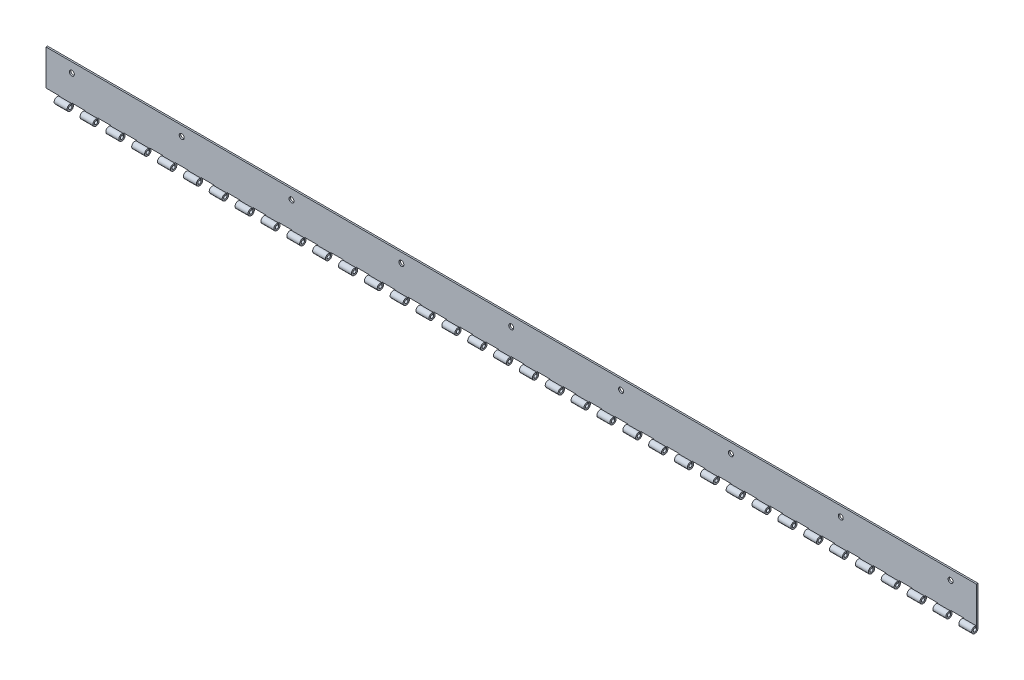
SolidWorks part; units mm, degrees
other "Bottom Leaf"
other "Top Leaf"
other "Pin" parameters "D1"=17.6771, "Angle"=25, "D2"=74.218, "Pin Diameter"=3.175, "D3"=51.2197, "Knuckle Diameter"=28.575, "Leaf Thickness"=1.524, "Overall Width"=76.2, "Length"=914.4, "Break Line"=152.4, "Knuckle Length"=12.7, "Chamfer"=0.3175
material "Plain Carbon Steel"
ref_plane "Front Plane" through (0, 0, 0) normal (0, 0, 1) x (1, 0, 0)
ref_plane "Top Plane" through (0, 0, 0) normal (0, 1, 0) x (1, 0, 0)
ref_plane "Right Plane" through (0, 0, 0) normal (1, 0, 0) x (0, 0, -1)
sketch "Sketch1" plane through (0, 0, 0) normal (1, 0, 0) x (0, 0, -1)
  line L0 (3.1115, 0) -> (3.1115, -38.1) construction
  line L1 (3.1115, -38.1) -> (1.5875, -38.1) construction
  line L2 (1.5875, -38.1) -> (1.5875, -2.6761) construction
  line L3 (0, 1.5875) -> (0, 3.1115) construction
  line L4 (0.6709, 1.4388) -> (1.315, 2.82) construction
  line L5 (0, -1.5875) -> (0, -3.1115) construction
  line L6 (0.6709, -1.4388) -> (1.315, -2.82) construction
  line L7 (3.1115, 0) -> (3.1115, 38.1) construction
  line L8 (3.1115, 38.1) -> (1.5875, 38.1) construction
  line L9 (1.5875, 38.1) -> (1.5875, 2.6761) construction
  line L10 (0, 3.1115) -> (3.1115, 3.1115) construction
  line L11 (0, -3.1115) -> (3.1115, -3.1115) construction
  line L12 (1.5875, -2.6761) -> (1.5875, 2.6761) construction
  line L13 (1.5875, 3.1369) -> (3.1115, 3.1369) construction
  circle A0 centre (0, 0) radius 1.5875 construction
  circle A1 centre (0, 0) radius 3.1115 construction
  point P3 (0, 1.5875)
  point P4 (0, -1.5875)
  point P5 (-1.5875, 0)
  point P6 (1.5875, 0)
  point P8 (-3.1115, 0)
  point P9 (0, 3.1115)
  point P10 (3.1115, 0)
  point P11 (0, -3.1115)
  point P17 (1.5875, -38.1)
  point P18 (3.1115, -38.1)
  point P22 (1.5875, -2.6761)
  point P24 (0.6709, 1.4388)
  point P25 (1.315, 2.82)
  point P30 (0.6709, -1.4388)
  point P31 (1.315, -2.82)
  point P34 (1.5875, 2.6761)
  point P36 (1.5875, 38.1)
  point P37 (3.1115, 38.1)
  point P40 (3.1115, -3.1115)
  point P41 (3.1115, 3.1115)
  point P44 (1.5875, 3.1369)
  point P45 (3.1115, 3.1369)
  dimension "D1" = 25
  dimension "Knuckle Diameter" = 6.223
  dimension "D2" = 0.0254
sketch "Sketch2" plane through (0, 0, 0) normal (0, 0, 1) x (1, 0, 0)
  line L0 (457.2, 38.1) -> (-457.2, 38.1) construction
  line L2 (457.2, -38.1) -> (-457.2, -38.1) construction
  line L4 (-457.2, -38.1) -> (-457.2, 38.1) construction
  line L5 (457.2, -38.1) -> (457.2, 38.1) construction
  line L6 (457.2, 3.1115) -> (-457.2, 3.1115) construction
  line L7 (-457.2, -3.1115) -> (457.2, -3.1115) construction
  line L8 (457.2, 0) -> (-457.2, 0) construction
  line L9 (304.8, -38.1) -> (304.8, 38.1) construction
  line L10 (-304.8, -38.1) -> (-304.8, 38.1) construction
  line L11 (0, -38.1) -> (0, 38.1) construction
  line L12 (457.2, 2.794) -> (456.8825, 3.1115) construction
  point P4 (0, 38.1)
  point P9 (0, -38.1)
  point P10 (-457.2, -38.1)
  point P12 (-457.2, 38.1)
  point P13 (457.2, -38.1)
  point P14 (457.2, 38.1)
  point P18 (444.5, -3.1115)
  point P19 (-457.2, -3.1115)
  point P20 (-457.2, 3.1115)
  point P21 (457.2, -3.1115)
  point P22 (457.2, 3.1115)
  point P28 (0, 0)
  point P30 (-457.2, 0)
  point P31 (457.2, 0)
  point P34 (304.8, 0)
  point P35 (304.8, -38.1)
  point P36 (304.8, 38.1)
  point P39 (-304.8, 0)
  point P40 (-304.8, 38.1)
  point P41 (-304.8, -38.1)
  point P44 (0, 0)
  point P45 (431.8, -3.1115)
  point P49 (456.8825, 3.1115)
  point P50 (457.2, 2.794)
  dimension "D1" = 12.7
  dimension "D2" = 45
ref_plane "Plane1" through (457.2, 0, 0) normal (1, 0, 0) x (0, 0, -1)
sketch "Sketch3" plane through (0, 0, 0) normal (1, 0, 0) x (0, 0, -1)
  line L2 (0.6709, -1.4388) -> (1.315, -2.82) construction
  line L3 (0.6709, -1.4388) -> (1.315, -2.82)
  line L4 (1.5875, -38.1) -> (1.5875, -2.6761) construction
  line L5 (1.5875, -38.1) -> (1.5875, -2.6761)
  line L6 (3.1115, 0) -> (3.1115, -38.1) construction
  line L7 (3.1115, 0) -> (3.1115, -38.1)
  line L8 (3.1115, -38.1) -> (1.5875, -38.1) construction
  line L9 (3.1115, -38.1) -> (1.5875, -38.1)
  line L10 (1.5875, 0) -> (1.5875, -2.6761)
  circle A0 centre (0, 0) radius 3.1115 construction
  arc A1 (3.1115, 0) -> (1.315, -2.82) centre (0, 0) ccw
  circle A2 centre (0, 0) radius 1.5875 construction
  arc A3 (1.5875, 0) -> (0.6709, -1.4388) centre (0, 0) ccw
extrude "Boss-Extrude1" add sketch "Sketch3" along normal mid plane 914.4
sketch "Sketch4" plane through (0, 0, 0) normal (0, 0, 1) x (1, 0, 0)
  line L0 (444.5, -3.1115) -> (444.5, 3.1115)
  line L1 (457.2, 3.1115) -> (-457.2, 3.1115) construction
  line L2 (444.5, 3.1115) -> (457.2, 3.1115)
  line L3 (457.2, 3.1115) -> (457.2, -3.1115)
  line L4 (457.2, -3.1115) -> (444.5, -3.1115)
extrude "Cut-Extrude1" cut sketch "Sketch4" against normal through all both and the other way through all
pattern_linear "LPattern1" count 36 spacing 25.4 along (-1, 0, 0) of "Cut-Extrude1"
sketch "Sketch5" plane through (457.2, 0, 0) normal (1, 0, 0) x (0, 0, -1)
  line L0 (1.5875, 38.1) -> (1.5875, 2.6761) construction
  line L1 (3.1115, 0) -> (3.1115, 38.1) construction
  line L3 (1.5875, 38.1) -> (1.5875, 2.6761)
  line L4 (3.1115, 0) -> (3.1115, 38.1)
  line L6 (3.1115, 38.1) -> (1.5875, 38.1) construction
  line L7 (3.1115, 38.1) -> (1.5875, 38.1)
  line L8 (0.6709, 1.4388) -> (1.315, 2.82) construction
  line L9 (0.6709, 1.4388) -> (1.315, 2.82)
  line L10 (1.5875, 2.6761) -> (1.5875, 0)
  circle A0 centre (0, 0) radius 1.5875 construction
  circle A1 centre (0, 0) radius 3.1115 construction
  arc A2 (0.6709, 1.4388) -> (1.5875, 0) centre (0, 0) ccw
  arc A3 (1.315, 2.82) -> (3.1115, 0) centre (0, 0) ccw
extrude "Boss-Extrude2" add sketch "Sketch5" against normal blind 914.4 separate body
sketch "Sketch6" plane through (0, 0, 0) normal (0, 0, 1) x (1, 0, 0)
  line L0 (431.8, -3.1115) -> (431.8, 3.1115)
  line L1 (457.2, 3.1115) -> (-457.2, 3.1115) construction
  line L2 (431.8, 3.1115) -> (444.5, 3.1115)
  line L3 (444.5, 3.1115) -> (444.5, -3.1115)
  line L4 (444.5, -3.1115) -> (431.8, -3.1115)
extrude "Cut-Extrude2" cut sketch "Sketch6" against normal through all both and the other way through all
pattern_linear "LPattern2" count 36 spacing 25.4 along (-1, 0, 0) of "Cut-Extrude2"
sketch "Sketch7" plane through (457.2, 0, 0) normal (1, 0, 0) x (0, 0, -1)
  circle A0 centre (0, 0) radius 1.5875 construction
  circle A1 centre (0, 0) radius 1.5875
extrude "Boss-Extrude3" add sketch "Sketch7" against normal blind 914.4 separate body
chamfer "Chamfer1" distance 0.3175 angle 45 2 edges at (-457.2, 0, -1.5875) (457.2, 0, -1.5875)
hole_wizard "#10 (0.1935) Diameter Hole1" positions "Sketch8" profile "Sketch9" hole size "#10" standard "ANSI Inch" end condition through all
sketch "Sketch8" plane through (0, 0, -1.5875) normal (0, 0, 1) x (1, 0, 0)
  line L0 (-457.2, 0) -> (457.2, 0) construction
  line L1 (-457.2, 3.1115) -> (-457.2, -3.1115) construction
  line L2 (457.2, -3.1115) -> (457.2, 3.1115) construction
  line L3 (-457.2, 0) -> (-457.2, -38.1) construction
  line L4 (-457.2, 38.1) -> (457.2, 38.1) construction
  point P0 (-431.8, -28.575)
  point P11 (-431.8, 28.575)
  point P17 (-323.85, -28.575)
  point P18 (-323.85, 28.575)
  point P19 (-215.9, -28.575)
  point P20 (-215.9, 28.575)
  point P21 (-107.95, -28.575)
  point P22 (-107.95, 28.575)
  point P23 (0, -28.575)
  point P24 (0, 28.575)
  point P25 (107.95, -28.575)
  point P26 (107.95, 28.575)
  point P27 (215.9, -28.575)
  point P28 (215.9, 28.575)
  point P29 (323.85, -28.575)
  point P30 (323.85, 28.575)
  point P31 (431.8, -28.575)
  point P32 (431.8, 28.575)
  dimension "D2" = 107.95
  dimension "D3" = 25.4
  dimension "D4" = 9.525
  dimension "D5" = 28.575
  dimension "D1" = 9
sketch "Sketch9" plane through (-431.8, -28.575, -1.5875) normal (1, 0, 0) x (0, -1, 0)
  line L0 (0, 0) -> (0, 1.524)
  line L1 (0, 1.524) -> (2.4574, 1.524)
  line L2 (2.4574, 1.524) -> (2.4574, 0)
  line L5 (2.4574, 0) -> (0, 0)
  line L11 (0, -6.35) -> (0, 107.95) construction
  dimension "Thru Hole Dia." = 4.9149
  dimension "Thru Hole Depth" = 1.524
delete or keep bodies "Body-Delete/Keep 1" type delete bodies bodies 184 140
delete or keep bodies "Body-Delete/Keep 2" [suppressed] type delete bodies bodies 140 185
delete or keep bodies "Body-Delete/Keep 3" [suppressed] type delete bodies bodies 185 185
equation "\"D1@Sketch1\"=\"Angle@Sketch1\""
equation "\"D1@Sketch2\"=\"Knuckle Length@Sketch2\""
equation "\"D1@Boss-Extrude1\" = \"Length@Sketch2\""
equation "\"D1@LPattern1\" = \"Length@Sketch2\" /  ( \"Knuckle Length@Sketch2\" * 2 ) "
equation "\"D3@LPattern1\" = \"Knuckle Length@Sketch2\" * 2"
equation "\"D1@Boss-Extrude2\"=\"Length@Sketch2\""
equation "\"Chamfer@Sketch2\" = \"Pin Diameter@Sketch1\" * .1"
equation "\"D1@Boss-Extrude3\" = \"Length@Sketch2\""
equation "\"D1@Chamfer1\"=\"Chamfer@Sketch2\""
equation "\"D3@LPattern2\" = \"Knuckle Length@Sketch2\" * 2"
equation "\"D1@LPattern2\" = \"Length@Sketch2\" /  ( \"Knuckle Length@Sketch2\" * 2 ) "
